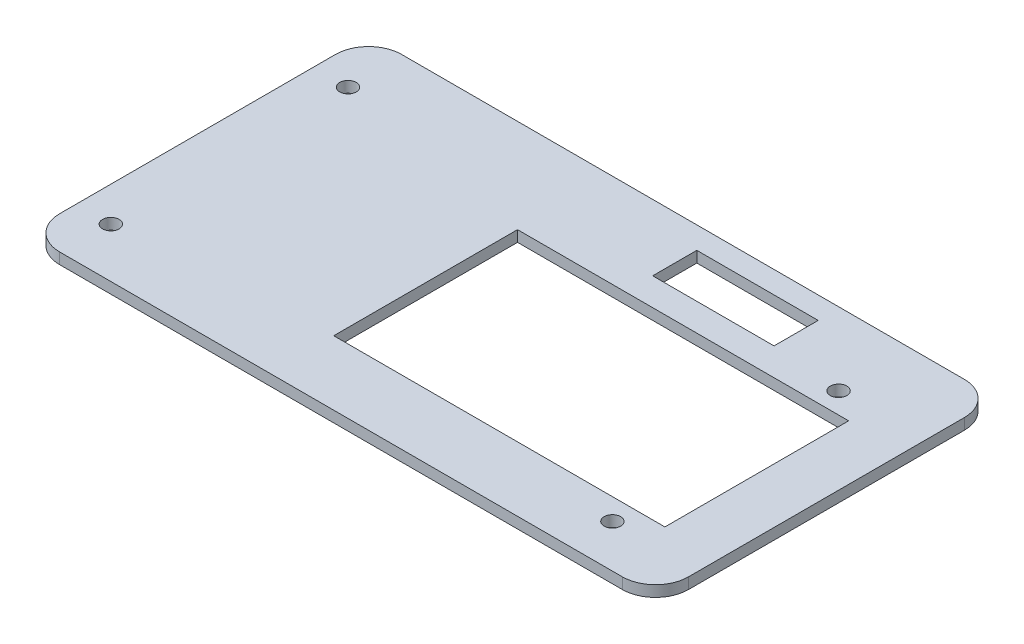
SolidWorks part; units mm, degrees
material "Плата обработки данных, простая"
ref_plane "Спереди" through (0, 0, 0) normal (0, 0, 1) x (1, 0, 0)
ref_plane "Сверху" through (0, 0, 0) normal (0, 1, 0) x (1, 0, 0)
ref_plane "Справа" through (0, 0, 0) normal (1, 0, 0) x (0, 0, -1)
sketch "Эскиз1" plane through (0, 0, 0) normal (0, 1, 0) x (1, 0, 0)
  line L0 (31.5, 0) -> (-82.5, 0) construction
  line L1 (-38.5, -19.3123) -> (21.5266, -19.3123)
  line L2 (-38.5, -19.3123) -> (-38.5, 14)
  line L3 (-38.5, 14) -> (21.5266, 14)
  line L4 (21.5266, -19.3123) -> (21.5266, 14)
  line L11 (-82.5, -31) -> (-82.5, -21)
  line L16 (31.5, 31) -> (-31.5, 31)
  line L17 (-82.5, 31) -> (-82.5, -21)
  line L18 (-82.5, -31) -> (31.5, -31)
  line L19 (31.5, 31) -> (31.5, -31)
  line L20 (-31.5, 31) -> (-82.5, 31)
  point P0 (0, 0)
  point P14 (31.5, 0)
extrude "Бобышка-Вытянуть1" add sketch "Эскиз1" along normal blind 2
sketch "Эскиз3" plane through (0, 2, 0) normal (0, -1, 0) x (1, 0, 0)
  line L0 (31.5, 0) -> (-82.5, 0) construction
  line L1 (31.5, 31) -> (31.5, -31) construction
  line L2 (-82.5, -31) -> (-82.5, 31) construction
  line L5 (3, -19) -> (3, -27)
  line L6 (3, -27) -> (-19, -27)
  line L7 (-19, -27) -> (-19, -19)
  line L8 (-19, -19) -> (3, -19)
  circle A0 centre (15.9, 23.2) radius 1.5
  circle A1 centre (15.9, -17.8) radius 1.5
  circle A2 centre (-76.22, 22) radius 1.5
  circle A3 centre (-76.22, -21) radius 1.5
  point P3 (0, 0)
extrude "Вырез-Вытянуть1" cut sketch "Эскиз3" along normal blind 10
fillet "Скругление1" radius 6 4 edges at (31.5, 1, -31) (31.5, 1, 31) (-82.5, 1, -31) (-82.5, 1, 31)
